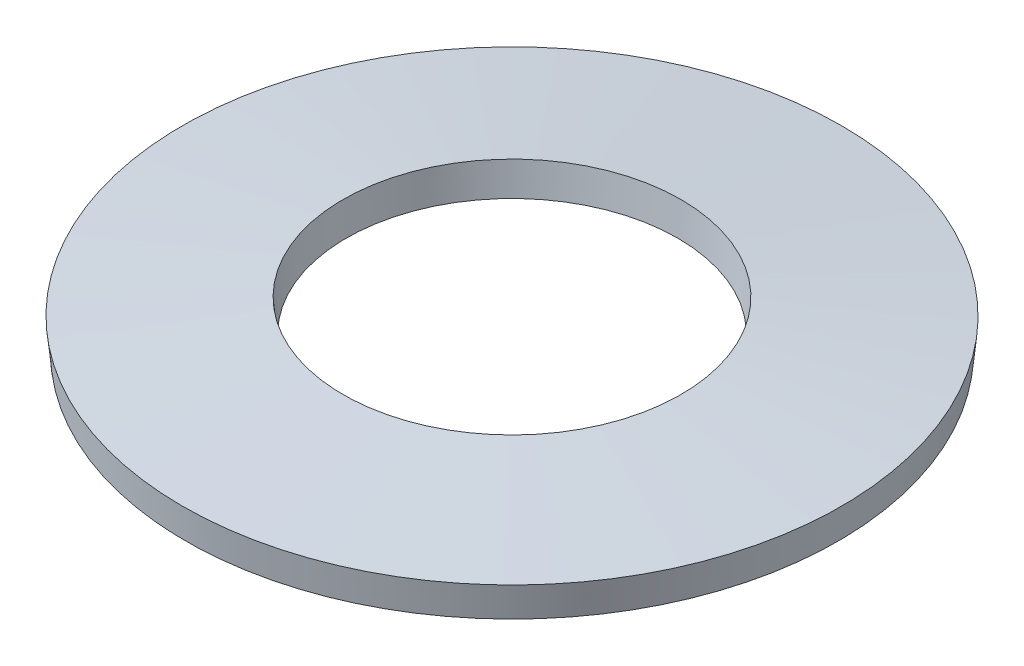
SolidWorks part; units mm, degrees
ref_plane "Front" through (0, 0, 0) normal (0, 0, 1) x (1, 0, 0)
ref_plane "Top" through (0, 0, 0) normal (0, 1, 0) x (1, 0, 0)
ref_plane "Right" through (0, 0, 0) normal (1, 0, 0) x (0, 0, -1)
sketch "Sketch1" plane through (0, 0, 0) normal (0, 0, 1) x (1, 0, 0)
  line L0 (22.0062, 0) -> (11.176, 1.1033)
  line L1 (11.176, 1.1033) -> (11.3948, 3.2512)
  line L2 (11.3948, 3.2512) -> (22.225, 2.1479)
  line L3 (22.225, 2.1479) -> (22.0062, 0)
  line L4 (0, 0) -> (0, 3.2512) construction
  dimension "ID" = 22.352
  dimension "OD" = 44.45
  dimension "Thickness" = 2.159
  dimension "Height" = 3.2512
revolve "Revolve1" add sketch "Sketch1" angle 360 about L4
